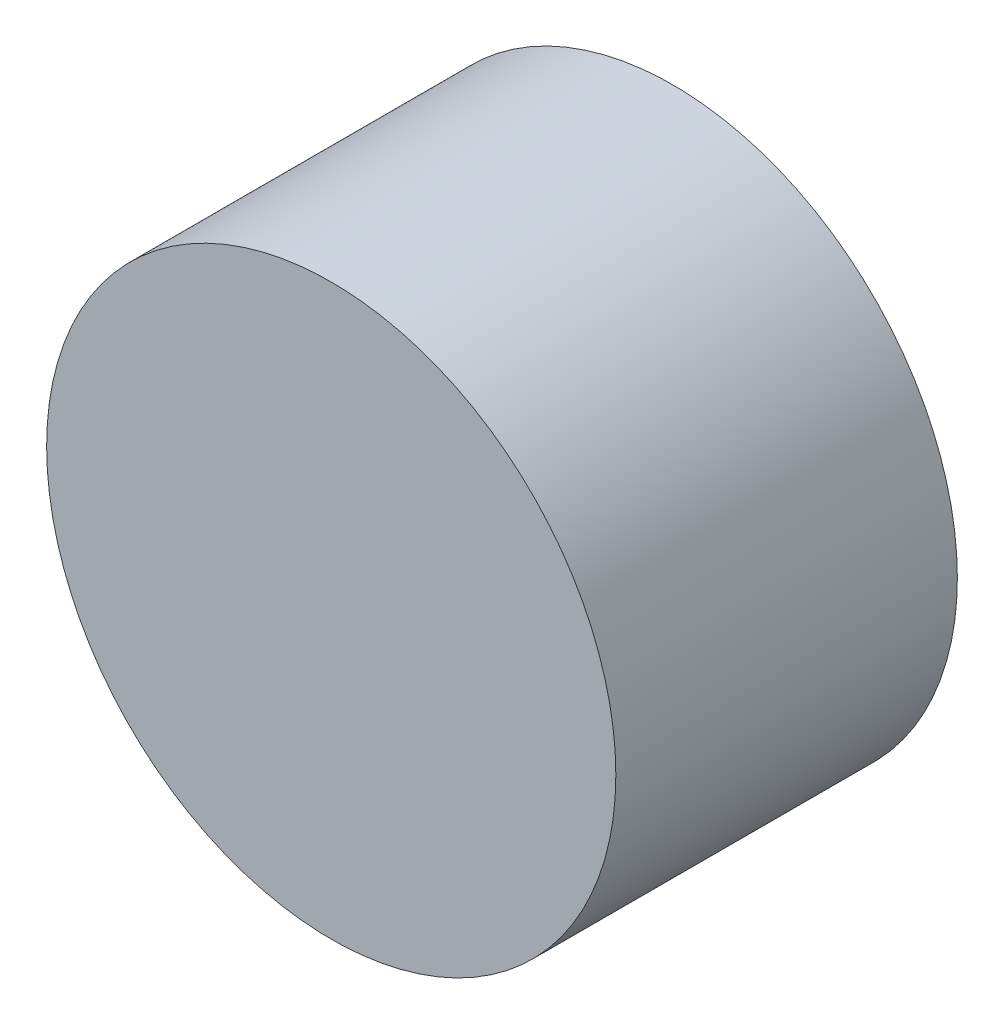
SolidWorks part; units mm, degrees
ref_plane "Alzado" through (0, 0, 0) normal (0, 0, 1) x (1, 0, 0)
ref_plane "Planta" through (0, 0, 0) normal (0, 1, 0) x (1, 0, 0)
ref_plane "Vista lateral" through (0, 0, 0) normal (1, 0, 0) x (0, 0, -1)
sketch "Croquis1" plane through (0, 0, 0) normal (0, 0, 1) x (1, 0, 0)
  circle A0 centre (0, 0) radius 2.5
  dimension "D1" = 5
extrude "Saliente-Extruir1" add sketch "Croquis1" along normal blind 3
